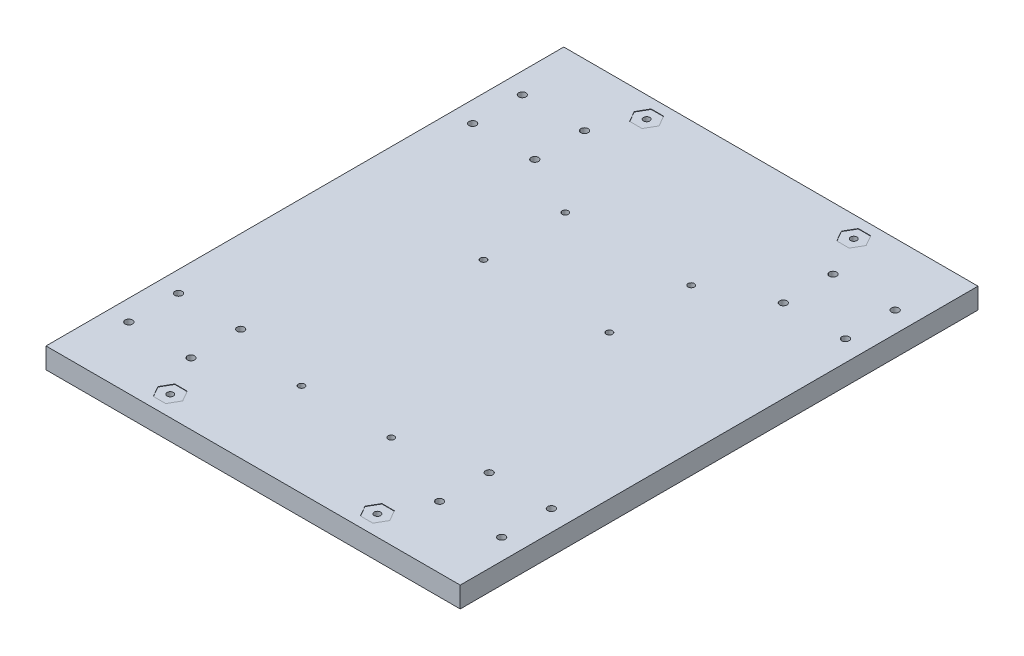
SolidWorks part; units mm, degrees
ref_plane "前视基准面" through (0, 0, 0) normal (0, 0, 1) x (1, 0, 0)
ref_plane "上视基准面" through (0, 0, 0) normal (0, 1, 0) x (1, 0, 0)
ref_plane "右视基准面" through (0, 0, 0) normal (1, 0, 0) x (0, 0, -1)
other "Configuration Table"
sketch "草图1" plane through (0, 0, 0) normal (0, 1, 0) x (1, 0, 0)
  line L0 (-98.7947, -125) -> (303.774, -125) construction
  line L1 (0, 0) -> (200, 0)
  line L2 (0, 0) -> (0, -250)
  line L3 (0, -250) -> (200, -250)
  line L4 (200, 0) -> (200, -250)
  line L5 (100, -311.2968) -> (100, 68.1358) construction
  line L6 (100, 61.2968) -> (100, -318.1358) construction
  circle A0 centre (180, -15) radius 4
  circle A1 centre (180, -235) radius 4
  circle A2 centre (20, -15) radius 4
  circle A3 centre (20, -235) radius 4
  dimension "D3" = 8
  dimension "D1" = 200
  dimension "D2" = 250
  dimension "D4" = 15
  dimension "D5" = 20
extrude "凸台-拉伸1" add sketch "草图1" along normal blind 10
sketch "草图2" plane through (0, 10, 0) normal (0, 1, 0) x (1, 0, 0)
  circle A0 centre (180, -235) radius 4 construction
  circle A1 centre (20, -235) radius 4 construction
  circle A2 centre (180, -15) radius 4 construction
  circle A3 centre (20, -15) radius 4 construction
  circle A4 centre (180, -235) radius 4
  circle A5 centre (20, -235) radius 4
  circle A6 centre (180, -15) radius 4
  circle A7 centre (20, -15) radius 4
extrude "凸台-拉伸3" add sketch "草图2" against normal blind 15
sketch "草图3" plane through (0, 10, 0) normal (0, 1, 0) x (1, 0, 0)
  line L0 (0, 0) -> (0, -250) construction
  line L1 (56, -240) -> (53, -234.8038)
  line L2 (53, -234.8038) -> (47, -234.8038)
  line L3 (47, -234.8038) -> (44, -240)
  line L4 (44, -240) -> (47, -245.1962)
  line L5 (47, -245.1962) -> (53, -245.1962)
  line L6 (53, -245.1962) -> (56, -240)
  line L7 (-138.8866, -125) -> (302.0889, -125) construction
  line L8 (100, -330.2848) -> (100, 59.0872) construction
  line L9 (0, -250) -> (200, -250) construction
  line L10 (200, 0) -> (0, 0) construction
  line L11 (200, -250) -> (200, 0) construction
  line L12 (147, -245.1962) -> (144, -240)
  line L13 (153, -245.1962) -> (147, -245.1962)
  line L14 (156, -240) -> (153, -245.1962)
  line L15 (153, -234.8038) -> (156, -240)
  line L16 (147, -234.8038) -> (153, -234.8038)
  line L17 (144, -240) -> (147, -234.8038)
  line L18 (144, -10) -> (147, -15.1962)
  line L19 (147, -15.1962) -> (153, -15.1962)
  line L20 (153, -15.1962) -> (156, -10)
  line L21 (156, -10) -> (153, -4.8038)
  line L22 (147, -4.8038) -> (144, -10)
  line L23 (53, -4.8038) -> (56, -10)
  line L24 (44, -10) -> (47, -4.8038)
  line L25 (47, -15.1962) -> (44, -10)
  line L26 (53, -15.1962) -> (47, -15.1962)
  line L27 (56, -10) -> (53, -15.1962)
  line L28 (47, -4.8038) -> (53, -4.8038)
  line L29 (147, -4.8038) -> (153, -4.8038)
  circle A1 centre (50, -240) radius 5.1962 construction
  circle A2 centre (150, -240) radius 5.1962 construction
  circle A3 centre (150, -10) radius 5.1962 construction
  circle A4 centre (50, -10) radius 5.1962 construction
  dimension "D1" = 6
  dimension "D2" = 50
  dimension "D3" = 10
extrude "切除-拉伸1" cut sketch "草图3" against normal blind 0.2
sketch "草图4" plane through (0, 10, 0) normal (0, 1, 0) x (1, 0, 0)
  line L0 (160.4995, -10) -> (136.67, -10) construction
  line L1 (150, 8.5602) -> (150, -30.1886) construction
  line L2 (50, 10.1394) -> (50, -44.3581) construction
  line L3 (41.2967, -240) -> (61.8094, -240) construction
  line L4 (53, -234.8038) -> (47, -234.8038) construction
  line L5 (47, -245.1962) -> (53, -245.1962) construction
  line L6 (147, -4.8038) -> (144, -10)
  line L7 (144, -10) -> (147, -15.1962)
  line L8 (147, -15.1962) -> (153, -15.1962)
  line L9 (153, -15.1962) -> (156, -10)
  line L10 (156, -10) -> (153, -4.8038)
  line L11 (153, -4.8038) -> (147, -4.8038)
  line L12 (147, -4.8038) -> (144, -10)
  line L13 (144, -10) -> (147, -15.1962)
  line L14 (147, -15.1962) -> (153, -15.1962)
  line L15 (153, -15.1962) -> (156, -10)
  line L16 (156, -10) -> (153, -4.8038)
  line L17 (153, -4.8038) -> (147, -4.8038)
  line L18 (53, -4.8038) -> (47, -4.8038)
  line L19 (47, -4.8038) -> (44, -10)
  line L20 (44, -10) -> (47, -15.1962)
  line L21 (47, -15.1962) -> (53, -15.1962)
  line L22 (53, -15.1962) -> (56, -10)
  line L23 (56, -10) -> (53, -4.8038)
  line L24 (53, -4.8038) -> (47, -4.8038)
  line L25 (47, -4.8038) -> (44, -10)
  line L26 (44, -10) -> (47, -15.1962)
  line L27 (47, -15.1962) -> (53, -15.1962)
  line L28 (53, -15.1962) -> (56, -10)
  line L29 (56, -10) -> (53, -4.8038)
  circle A0 centre (150, -10) radius 1.525
  circle A1 centre (50, -10) radius 1.525
  circle A2 centre (50, -240) radius 1.525
  circle A3 centre (150, -240) radius 1.525
  dimension "D2" = 3.05
  dimension "D4" = 3.05
  dimension "D5" = 3.05
  dimension "D6" = 3.05
  dimension "D1" = 0
  dimension "D3" = 0
extrude "切除-拉伸2" cut sketch "草图4" against normal through all contours A1 | A0 | A3 | A2
sketch "草图5" plane through (0, 10, 0) normal (0, 1, 0) x (1, 0, 0)
  line L0 (100, 76.7969) -> (100, -349.7043) construction
  line L1 (239.5619, -125) -> (-59.6589, -125) construction
  line L2 (157.1542, -88.6132) -> (46.9995, -88.6132) construction
  line L3 (135, -66.1132) -> (65, -66.1132) construction
  line L4 (0, 0) -> (0, -250)
  line L5 (0, -250) -> (200, -250)
  line L6 (200, -250) -> (200, 0)
  line L7 (200, 0) -> (0, 0)
  line L8 (0, 0) -> (0, -250) construction
  line L9 (0, -250) -> (200, -250) construction
  line L10 (200, -250) -> (200, 0) construction
  line L11 (200, 0) -> (0, 0) construction
  line L12 (135, -66.1132) -> (135, -111.1132) construction
  line L13 (135, -111.1132) -> (65, -111.1132) construction
  line L14 (65, -66.1132) -> (65, -111.1132) construction
  line L15 (135, -66.1132) -> (65, -111.1132) construction
  line L16 (135, -111.1132) -> (65, -66.1132) construction
  circle A0 centre (69.6, -68.8632) radius 1.5
  circle A1 centre (69.6, -108.3632) radius 1.5
  circle A2 centre (130.4, -108.3632) radius 1.5
  circle A3 centre (130.4, -68.8632) radius 1.5
  point P8 (100, -88.6132)
  dimension "D4" = 3
  dimension "D2" = 45
  dimension "D3" = 70
  dimension "D5" = 39.5
  dimension "D6" = 60.8
  dimension "D1" = 0
extrude "切除-拉伸3" cut sketch "草图5" against normal through all
sketch "草图6" plane through (0, 10, 0) normal (0, 1, 0) x (1, 0, 0)
  line L0 (200, -250) -> (200, 0) construction
  line L1 (200, 0) -> (0, 0) construction
  line L2 (0, -250) -> (200, -250) construction
  line L3 (0, 0) -> (0, -250) construction
  circle A0 centre (190, -54) radius 1.75
  circle A2 centre (160, -54) radius 1.75
  circle A4 centre (160, -30) radius 1.75
  circle A5 centre (190, -30) radius 1.75
  circle A6 centre (190, -220) radius 1.75
  circle A7 centre (160, -220) radius 1.75
  circle A8 centre (160, -196) radius 1.75
  circle A9 centre (190, -196) radius 1.75
  circle A10 centre (40, -54) radius 1.75
  circle A11 centre (10, -54) radius 1.75
  circle A12 centre (10, -30) radius 1.75
  circle A13 centre (40, -30) radius 1.75
  circle A14 centre (40, -220) radius 1.75
  circle A15 centre (10, -220) radius 1.75
  circle A16 centre (10, -196) radius 1.75
  circle A17 centre (40, -196) radius 1.75
  dimension "D13" = 3.5
  dimension "D14" = 3.5
  dimension "D15" = 3.5
  dimension "D18" = 3.5
  dimension "D1" = 24
  dimension "D2" = 30
  dimension "D3" = 10
  dimension "D4" = 24
  dimension "D5" = 30
  dimension "D6" = 24
  dimension "D7" = 30
  dimension "D8" = 24
  dimension "D9" = 30
  dimension "D10" = 10
  dimension "D11" = 30
  dimension "D12" = 30
  dimension "D16" = 30
  dimension "D17" = 10
  dimension "D19" = 10
  dimension "D20" = 30
extrude "切除-拉伸4" cut sketch "草图6" against normal through all
sketch "草图7" plane through (0, 10, 0) normal (0, 1, 0) x (1, 0, 0)
  line L0 (100, -266.7628) -> (100, 44.0137) construction
  line L1 (0, -250) -> (200, -250) construction
  circle A0 centre (121.65, -205) radius 1.5
  circle A1 centre (78.35, -205) radius 1.5
  dimension "D1" = 43.3
  dimension "D3" = 3
  dimension "D2" = 45
extrude "切除-拉伸5" cut sketch "草图7" against normal through all
